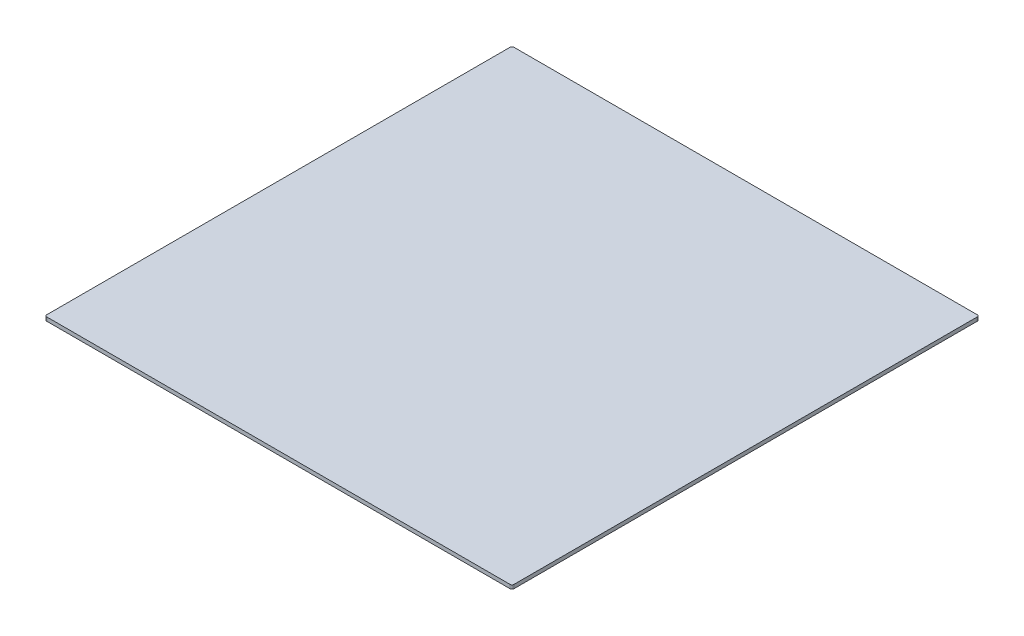
SolidWorks part; units mm, degrees
material "Beryllium Copper, UNS C17000"
ref_plane "Front Plane" through (0, 0, 0) normal (0, 0, 1) x (1, 0, 0)
ref_plane "Top Plane" through (0, 0, 0) normal (0, 1, 0) x (1, 0, 0)
ref_plane "Right Plane" through (0, 0, 0) normal (1, 0, 0) x (0, 0, -1)
sketch "Sketch1" plane through (0, 0, 0) normal (0, 1, 0) x (1, 0, 0)
  line L1 (-123.5, -123.5) -> (123.5, -123.5)
  line L2 (-123.5, -123.5) -> (-123.5, 123.5)
  line L3 (-123.5, 123.5) -> (123.5, 123.5)
  line L4 (123.5, -123.5) -> (123.5, 123.5)
  line L5 (-123.5, -123.5) -> (123.5, 123.5) construction
  line L6 (-123.5, 123.5) -> (123.5, -123.5) construction
  point P0 (0, 0)
  dimension "D1" = 247
extrude "Boss-Extrude1" add sketch "Sketch1" along normal mid plane 2
fillet "Fillet1" radius 1 4 edges at (-123.5, 0, 123.5) (-123.5, 0, -123.5) (123.5, 0, -123.5) (123.5, 0, 123.5)
